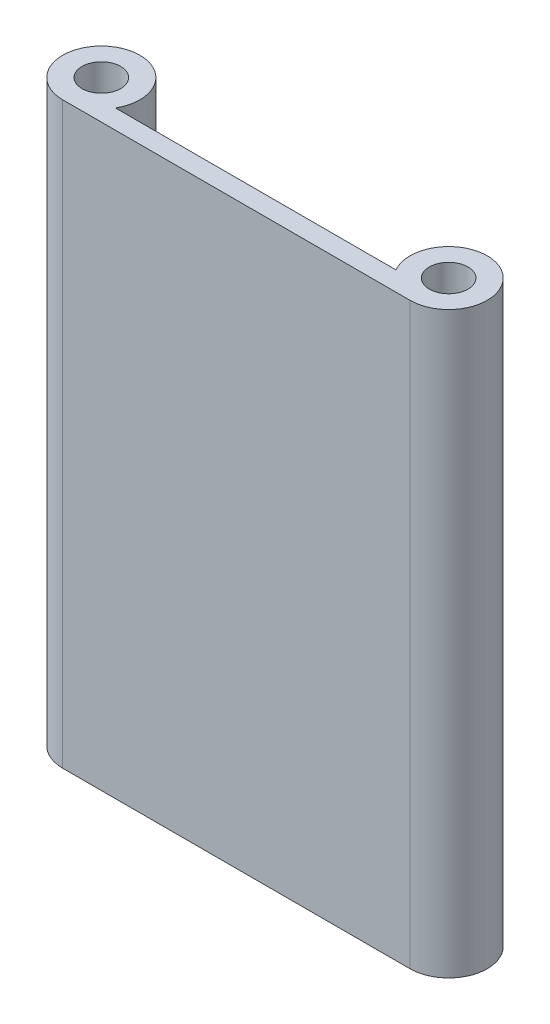
SolidWorks part; units mm, degrees
ref_plane "Front Plane" through (0, 0, 0) normal (0, 0, 1) x (1, 0, 0)
ref_plane "Top Plane" through (0, 0, 0) normal (0, 1, 0) x (1, 0, 0)
ref_plane "Right Plane" through (0, 0, 0) normal (1, 0, 0) x (0, 0, -1)
sketch "Sketch1" plane through (0, 0, 0) normal (0, 1, 0) x (1, 0, 0)
  line L1 (-28.575, -1.7565) -> (28.575, -1.7565)
  line L3 (-23.0757, 1.4185) -> (23.0757, 1.4185)
  line L5 (-28.575, -1.7565) -> (23.0757, 1.4185) construction
  line L6 (-23.0757, 1.4185) -> (28.575, -1.7565) construction
  circle A0 centre (0, 0) radius 36.576 construction
  arc A1 (28.575, -1.7565) -> (23.0757, 1.4185) centre (28.575, 4.5935) ccw
  arc A2 (-23.0757, 1.4185) -> (-28.575, -1.7565) centre (-28.575, 4.5935) ccw
  circle A3 centre (-28.575, 4.5935) radius 3.175
  circle A4 centre (28.575, 4.5935) radius 3.175
  dimension "D1" = 73.152
  dimension "D2" = 12.7
  dimension "D3" = 12.7
  dimension "D6" = 6.35
  dimension "D7" = 6.35
  dimension "D4" = 57.15
  dimension "D5" = 3.175
extrude "Boss-Extrude1" add sketch "Sketch1" along normal blind 95.25
equation "\"airframeInnerDiameter\"=3"
equation "\"outerDiameter\"=3.124"
equation "\"airframeBulkheadThickness\"=0.125"
equation "\"payloadAirframeLength\"=5"
equation "\"payloadCouplerInnerDiameter\"=2.88"
equation "\"payloadCouplerLength\"=5.5"
equation "\"payloadCouplerBandLength\"=1"
equation "\"payloadCouplerOuter\"=\"airframeInnerDiameter\""
equation "\"payloadCouplerOffsetFromAft\"=3"
equation "\"upperAirframeLength\"=12.5"
equation "\"recoveryBayInnerDiameter\"=2.88"
equation "\"recoveryBayLength\"=4"
equation "\"recoveryBandLength\"=1"
equation "\"recoveryCouplerOuter\"=\"airframeInnerDiameter\""
equation "\"recoveryOffsetFromAft\"=1.5"
equation "\"midAirframeLength\"=10"
equation "\"ATSBayInnerDiameter\"=2.88"
equation "\"ATSBayLength\"=5.5"
equation "\"ATSBandLength\"=1"
equation "\"ATSCouplerOuter\"=\"airframeInnerDiameter\""
equation "\"ATSOffsetFromAft\"=1.5"
equation "\"lowerAirframeLength\"=20"
equation "\"finSlotLength\"=4.1875"
equation "\"finSlotOffsetFromAft\"=1.5"
equation "\"finSlotWidth\"=0.125"
equation "\"D1@Sketch1\"=\"recoveryBayInnerDiameter\""
